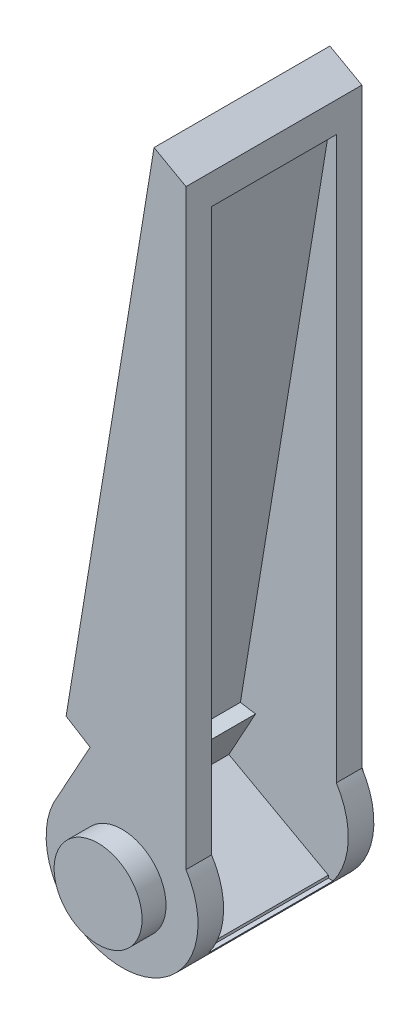
SolidWorks part; units mm, degrees
ref_plane "Plan de face" through (0, 0, 0) normal (0, 0, 1) x (1, 0, 0)
ref_plane "Plan de dessus" through (0, 0, 0) normal (0, 1, 0) x (1, 0, 0)
ref_plane "Plan de droite" through (0, 0, 0) normal (1, 0, 0) x (0, 0, -1)
sketch "Esquisse1" plane through (0, 0, 0) normal (0, 0, 1) x (1, 0, 0)
  line L0 (4, 2.5617) -> (4, 39.5617)
  line L1 (4, 39.5617) -> (2, 40.6792)
  line L2 (2, 40.6792) -> (-3.5, 7.127)
  line L3 (-3.5, 7.127) -> (-2, 6.1931)
  line L4 (-2, 6.1931) -> (-4, 2.5617)
  arc A0 (-4, 2.5617) -> (4, 2.5617) centre (0, 0) ccw
  dimension "D1" = 4.75
  dimension "D2" = 8
  dimension "D3" = 37
  dimension "D4" = 2
  dimension "D5" = 7.5
  dimension "D6" = 34
  dimension "D7" = 6
  dimension "D8" = 4.1457
  dimension "D9" = 1.767
extrude "Boss.-Extru.1" add sketch "Esquisse1" along normal blind 11
sketch "Esquisse2" plane through (0, 0, 0) normal (0, 0, 1) x (1, 0, 0)
  circle A0 centre (0, 0) radius 2.75
  dimension "D1" = 5.5
extrude "Boss.-Extru.2" add sketch "Esquisse2" against normal blind 1.5
sketch "Esquisse3" plane through (0, 0, 11) normal (0, 0, 1) x (1, 0, 0)
  circle A0 centre (0, 0) radius 2.75
  dimension "D1" = 5.5
extrude "Boss.-Extru.3" add sketch "Esquisse3" along normal blind 1.5
ref_plane "Plan1" through (14, 0, 0) normal (1, 0, 0) x (0, 0, -1)
sketch "Esquisse5" plane through (14, 0, 0) normal (1, 0, 0) x (0, 0, -1)
  line L0 (-11, 40.6792) -> (0, 40.6792) construction
  line L1 (-9.4, 37.6792) -> (-1.6, 37.6792)
  line L2 (-9.4, 37.6792) -> (-9.4, -2.85)
  line L3 (-9.4, -2.85) -> (-1.6, -2.85)
  line L4 (-1.6, 37.6792) -> (-1.6, -2.85)
  line L5 (-9.4, 37.6792) -> (-1.6, -2.85) construction
  line L6 (-9.4, -2.85) -> (-1.6, 37.6792) construction
  line L7 (0, 2.5617) -> (0, 39.5617) construction
  line L8 (-11, 2.5617) -> (-11, 39.5617) construction
  line L9 (-11, -4.75) -> (0, -4.75) construction
  point P0 (-5.5, 17.4146)
  dimension "D1" = 3
  dimension "D2" = 1.6
  dimension "D3" = 1.6
  dimension "D4" = 1.9
extrude "Enlèv. mat.-Extru.1" cut sketch "Esquisse5" against normal blind 10.5
ref_plane "Plan2" through (4.6078, -2.5378, 0) normal (-0.8759, 0.4824, 0) x (0, 0, 1)
sketch "Esquisse6" plane through (4.6078, -2.5378, 0) normal (-0.8759, 0.4824, 0) x (0, 0, 1)
  line L0 (9.4, 4.1736) -> (9.4, -0.6632) construction
  line L1 (9.4, 4.3368) -> (1.6, 4.3368)
  line L2 (9.4, 4.3368) -> (9.4, -0.6632)
  line L3 (9.4, -0.6632) -> (1.6, -0.6632)
  line L4 (1.6, 4.3368) -> (1.6, -0.6632)
  line L5 (9.4, 4.3368) -> (1.6, -0.6632) construction
  line L6 (9.4, -0.6632) -> (1.6, 4.3368) construction
  line L7 (1.6, -0.8079) -> (1.6, 34.6931) construction
  line L8 (1.6, -0.6632) -> (9.4, -0.6632) construction
  point P0 (5.5, 1.8368)
  point P5 (9.4, 1.8368)
  dimension "D1" = 5
extrude "Enlèv. mat.-Extru.2" cut sketch "Esquisse6" along normal blind 8
ref_plane "Plan3" through (5.3222, -0.8724, 0) normal (-0.9868, 0.1618, 0) x (0, 0, 1)
sketch "Esquisse7" plane through (5.3222, -0.8724, 0) normal (-0.9868, 0.1618, 0) x (0, 0, 1)
  line L1 (9.4, 37.83) -> (1.6, 37.83)
  line L2 (9.4, 37.83) -> (9.4, 3.5498)
  line L3 (9.4, 3.5498) -> (1.6, 3.5498)
  line L4 (1.6, 37.83) -> (1.6, 3.5498)
  line L5 (9.4, 37.83) -> (1.6, 3.5498) construction
  line L6 (9.4, 3.5498) -> (1.6, 37.83) construction
  line L7 (9.4, 3.5498) -> (1.6, 3.5498) construction
  line L8 (9.4, 3.1751) -> (9.4, 37.83) construction
  line L10 (1.6, 37.83) -> (1.6, 3.1751) construction
  line L11 (9.4, 37.83) -> (1.6, 37.83) construction
  point P0 (5.5, 20.6899)
extrude "Enlèv. mat.-Extru.3" cut sketch "Esquisse7" along normal blind 8
